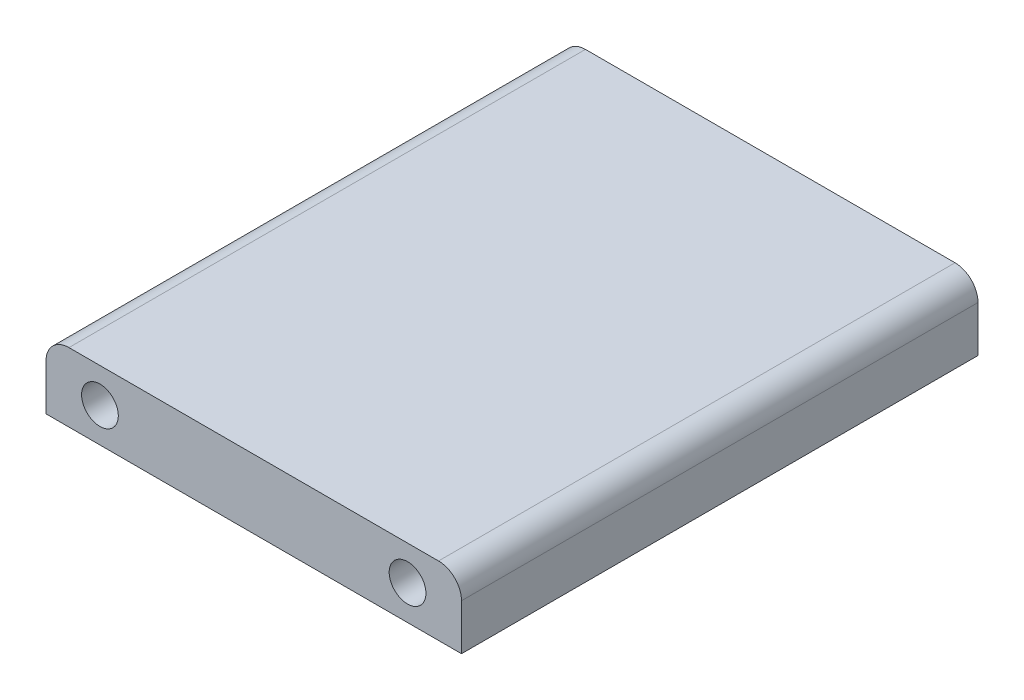
SolidWorks part; units mm, degrees
material "Thornel VCB-20 Carbon Cloth"
ref_plane "Front Plane" through (0, 0, 0) normal (0, 0, 1) x (1, 0, 0)
ref_plane "Top Plane" through (0, 0, 0) normal (0, 1, 0) x (1, 0, 0)
ref_plane "Right Plane" through (0, 0, 0) normal (1, 0, 0) x (0, 0, -1)
sketch "Sketch1" plane through (0, 0, 0) normal (0, 1, 0) x (1, 0, 0)
  line L1 (-18.1, -22.5) -> (18.1, -22.5)
  line L2 (-18.1, -22.5) -> (-18.1, 22.5)
  line L3 (-18.1, 22.5) -> (18.1, 22.5)
  line L4 (18.1, -22.5) -> (18.1, 22.5)
  line L5 (-18.1, -22.5) -> (18.1, 22.5) construction
  line L6 (-18.1, 22.5) -> (18.1, -22.5) construction
  point P0 (0, 0)
  dimension "D1" = 45
  dimension "D2" = 36.2
extrude "Boss-Extrude1" add sketch "Sketch1" along normal blind 6
fillet "Fillet1" radius 2 2 edges at (18.1, 6, 0) (-18.1, 6, 0)
sketch "Sketch3" plane through (0, 0, 22.5) normal (0, 0, 1) x (1, 0, 0)
  line L0 (0, 0) -> (0, 6) construction
  line L1 (-16.1, 6) -> (16.1, 6) construction
  line L2 (0, 3) -> (-13.4, 3) construction
  circle A0 centre (-13.4, 3) radius 1.6
  circle A1 centre (13.4, 3) radius 1.6
  dimension "D2" = 3.2
  dimension "D1" = 13.4
extrude "Cut-Extrude1" cut sketch "Sketch3" against normal through all
